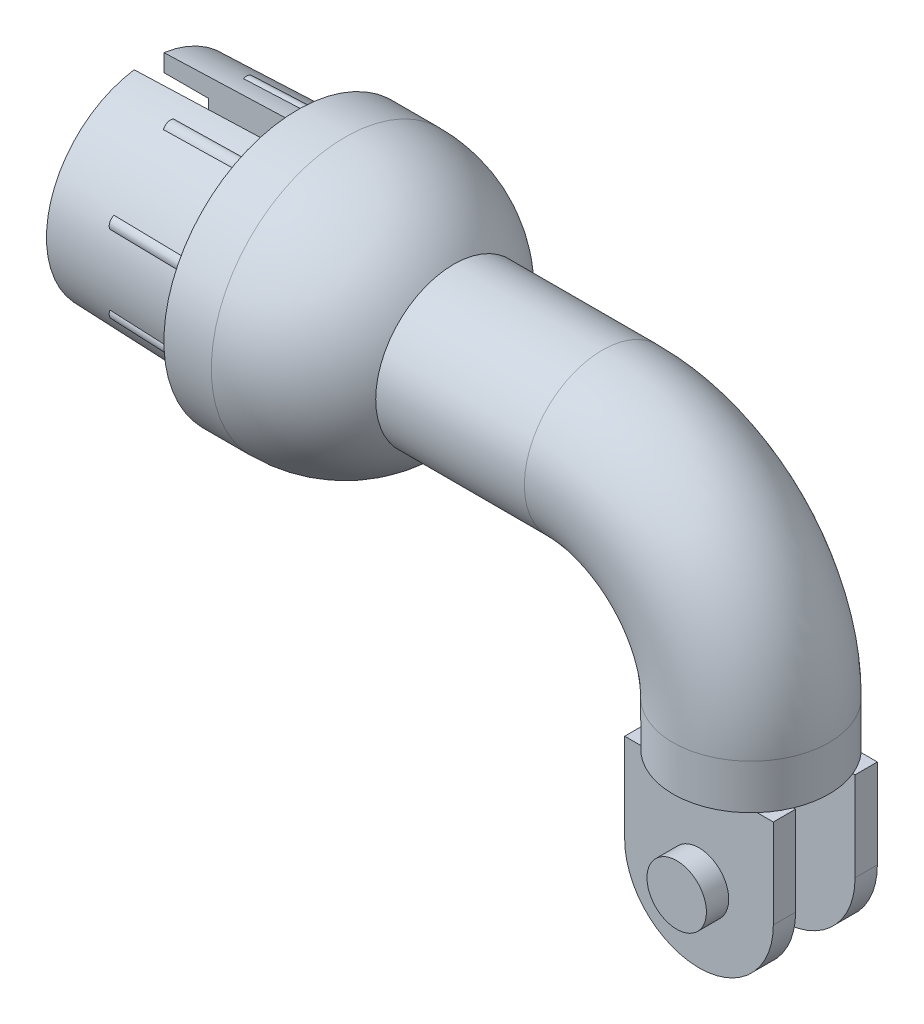
SolidWorks part; units mm, degrees
ref_plane "Front" through (0, 0, 0) normal (0, 0, 1) x (1, 0, 0)
ref_plane "Top" through (0, 0, 0) normal (0, 1, 0) x (1, 0, 0)
ref_plane "Right" through (0, 0, 0) normal (1, 0, 0) x (0, 0, -1)
ref_plane "Plane4" through (0, 6, 0) normal (0, 1, 0) x (-1, 0, 0)
sketch "Sketch1" plane through (0, 6, 0) normal (0, 1, 0) x (-1, 0, 0)
  circle A0 centre (0, 0) radius 5.25
  dimension "D1" = 10.5
sketch "Sketch2" plane through (0, 0, 0) normal (0, 0, 1) x (1, 0, 0)
  line L0 (0, 6) -> (0, 9)
  line L1 (-10, 19) -> (-25, 19)
  line L2 (50, 6) -> (-50, 6) construction
  arc A0 (-10, 19) -> (0, 9) centre (-10, 9) cw
  point P8 (0, 19)
  dimension "D3" = 10
  dimension "D1" = 13
  dimension "D2" = 25
sweep "Base-Sweep" add profiles "Sketch1" path "Sketch2"
sketch "Sketch3" plane through (0, 0, 0) normal (0, 0, 1) x (1, 0, 0)
  line L0 (-36.1722, 19) -> (-64.353, 19) construction
  line L1 (-10, 19) -> (-25, 19) construction
  line L2 (-27.3101, 28) -> (-30.5, 28)
  line L3 (-30.5, 28) -> (-30.5, 19)
  line L4 (-30.5, 19) -> (-18.3101, 19)
  line L5 (0, -50) -> (0, 50) construction
  line L6 (-10, 24.25) -> (-25, 24.25) construction
  line L7 (-10, 24.25) -> (-25, 24.25) construction
  arc A0 (-18.3101, 19) -> (-27.3101, 28) centre (-27.3101, 19) ccw
  point P13 (-20, 24.25)
  dimension "D3" = 9
  dimension "D1" = 18
  dimension "D2" = 30.5
  dimension "D4" = 3.1899
  dimension "D5" = 20
revolve "Boss-Revolve1" add sketch "Sketch3" angle 360 about L0
sketch "Sketch4" plane through (-30.5, 0, 0) normal (-1, 0, 0) x (0, 0, 1)
  circle A0 centre (0, 19) radius 7.25
  dimension "D1" = 14.5
extrude "Boss-Extrude1" add sketch "Sketch4" along normal blind 10 draft 2
shell "Shell1" thickness 2
ref_plane "Plane5" through (0, 2.7825, 6.7175) normal (0, 0.3827, 0.9239) x (1, 0, 0)
sketch "Sketch6" plane through (0, 2.7825, 6.7175) normal (0, 0.3827, 0.9239) x (1, 0, 0)
  line L0 (-36.5, 24.5942) -> (-30.5, 24.8037)
  line L1 (-30.5, 24.8037) -> (-40.5, 24.4545) construction
  dimension "D1" = 6
sketch "Sketch7" plane through (-30.5, 0, 0) normal (-1, 0, 0) x (0, 0, 1)
  line L0 (12.0792, -10.1618) -> (1.3558, 15.7268) construction
  line L1 (-2.6405, 25.3748) -> (-2.8942, 25.9871) construction
  circle A0 centre (-2.6405, 25.3748) radius 0.5
  circle A1 centre (0, 19) radius 7.25 construction
  circle A2 centre (0, 19) radius 7.25 construction
  dimension "D1" = 1
  dimension "D2" = 0.15
sweep "Boss-Sweep1" add profiles "Sketch7" path "Sketch6"
pattern_circular "CirPattern1" count 8 over 360 about axis through (-36.1722, 19, 0) along (-1, 0, 0) of "Boss-Sweep1"
sketch "Sketch8" plane through (-40.5, 0, 0) normal (-1, 0, 0) x (0, 0, 1)
  circle A0 centre (0, 19) radius 5.75
  dimension "D1" = 11.5
extrude "Cut-Extrude1" cut sketch "Sketch8" against normal blind 3
sketch "Sketch9" plane through (0, 0, 0) normal (0, 1, 0) x (1, 0, 0)
  line L1 (-31.1, 1) -> (-31.1, -1)
  line L2 (-40.5, 1) -> (-31.1, 1)
  line L3 (-40.5, 1) -> (-40.5, -1)
  line L4 (-31.1, -1) -> (-40.5, -1)
  line L5 (-50, 0) -> (50, 0) construction
  line L6 (-40.5, 6.9008) -> (-40.5, -6.9008) construction
  line L7 (-30.5, 9) -> (-30.5, -9) construction
  point P5 (-40.5, 0)
  dimension "D1" = 2
  dimension "D2" = 0.6
extrude "Cut-Extrude2" cut sketch "Sketch9" along normal through all
ref_plane "Plane6" through (0, 0, -3.5) normal (0, 0, 1) x (1, 0, 0)
sketch "Sketch10" plane through (0, 12.319, -3.5) normal (0, 0, -1) x (1, 0, 0)
  line L0 (-5, 6.319) -> (5, 6.319)
  line L1 (-5, 6.319) -> (-5, 12.319)
  line L3 (5, 12.319) -> (5, 6.319)
  line L4 (0, -37.681) -> (0, 62.319) construction
  line L5 (5.25, 6.319) -> (-5.25, 6.319) construction
  arc A0 (-5, 12.319) -> (5, 12.319) centre (0, 12.319) cw
  dimension "D1" = 10
  dimension "D2" = 11
extrude "Boss-Extrude2" add sketch "Sketch10" against normal blind 1.5
sketch "Sketch11" plane through (0, 0, -3.5) normal (0, 0, -1) x (-1, 0, 0)
  circle A0 centre (0, 0) radius 2
  dimension "D1" = 4
extrude "Boss-Extrude3" add sketch "Sketch11" along normal blind 1.5
mirror "Mirror1" about plane through (0, 0, 0) normal (0, 0, 1) of "Boss-Extrude3", "Boss-Extrude2"
